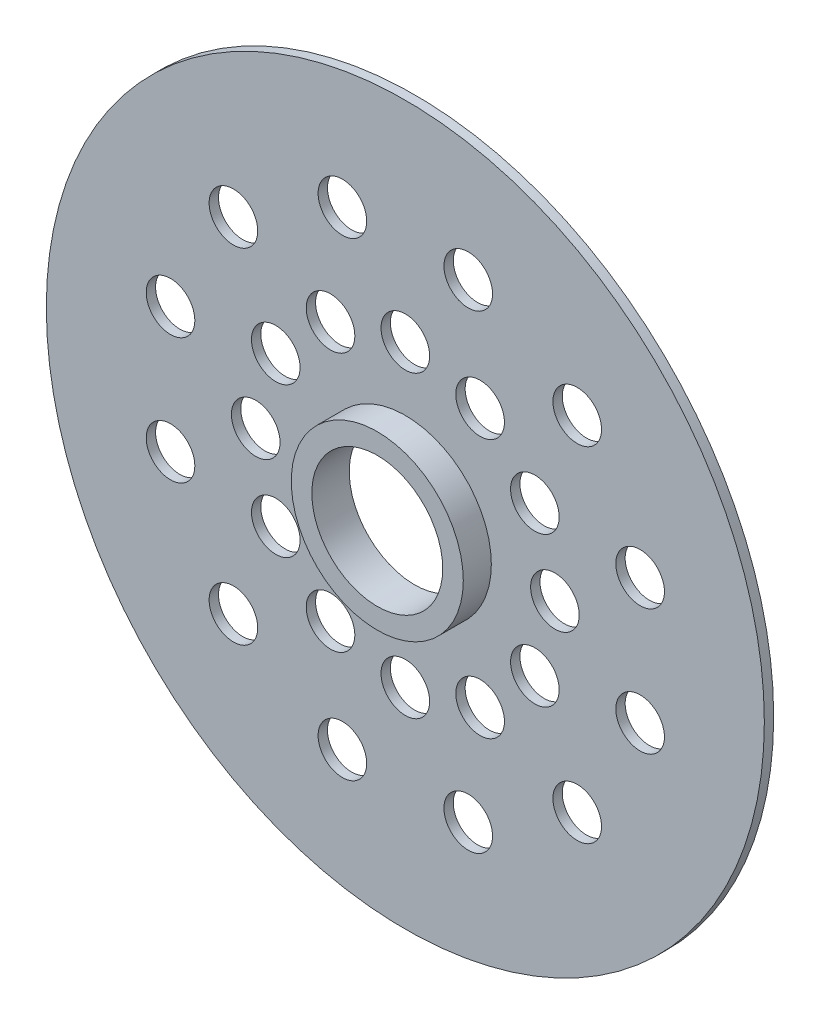
SolidWorks part; units mm, degrees
ref_plane "Спереди" through (0, 0, 0) normal (0, 0, 1) x (1, 0, 0)
ref_plane "Сверху" through (0, 0, 0) normal (0, 1, 0) x (1, 0, 0)
ref_plane "Справа" through (0, 0, 0) normal (1, 0, 0) x (0, 0, -1)
sketch "Эскиз1" plane through (0, 0, 0) normal (0, 0, 1) x (1, 0, 0)
  circle A0 centre (0, 0) radius 96
  circle A1 centre (0, 0) radius 17.5
extrude "Rear_cover_reference" add sketch "Эскиз1" along normal blind 2.5 from offset 47
sketch "Эскиз2" plane through (0, 0, 0) normal (0, 0, 1) x (1, 0, 0)
  circle A0 centre (0, 0) radius 23
  circle A1 centre (0, 0) radius 17.5
extrude "Bearing_boss_reference" add sketch "Эскиз2" along normal blind 10 from offset 47
sketch "Эскиз3" plane through (0, 0, 0) normal (0, 0, 1) x (1, 0, 0)
  circle A0 centre (40, 0) radius 6.5
  circle A1 centre (34.641, 20) radius 6.5
  circle A2 centre (20, 34.641) radius 6.5
  circle A3 centre (0, 40) radius 6.5
  circle A4 centre (-20, 34.641) radius 6.5
  circle A5 centre (-34.641, 20) radius 6.5
  circle A6 centre (-40, 0) radius 6.5
  circle A7 centre (-34.641, -20) radius 6.5
  circle A8 centre (-20, -34.641) radius 6.5
  circle A9 centre (0, -40) radius 6.5
  circle A10 centre (20, -34.641) radius 6.5
  circle A11 centre (34.641, -20) radius 6.5
  circle A12 centre (62.7852, 16.8232) radius 6.5
  circle A13 centre (45.9619, 45.9619) radius 6.5
  circle A14 centre (16.8232, 62.7852) radius 6.5
  circle A15 centre (-16.8232, 62.7852) radius 6.5
  circle A16 centre (-45.9619, 45.9619) radius 6.5
  circle A17 centre (-62.7852, 16.8232) radius 6.5
  circle A18 centre (-62.7852, -16.8232) radius 6.5
  circle A19 centre (-45.9619, -45.9619) radius 6.5
  circle A20 centre (-16.8232, -62.7852) radius 6.5
  circle A21 centre (16.8232, -62.7852) radius 6.5
  circle A22 centre (45.9619, -45.9619) radius 6.5
  circle A23 centre (62.7852, -16.8232) radius 6.5
extrude "Through_holes" cut sketch "Эскиз3" against normal mid plane 200
